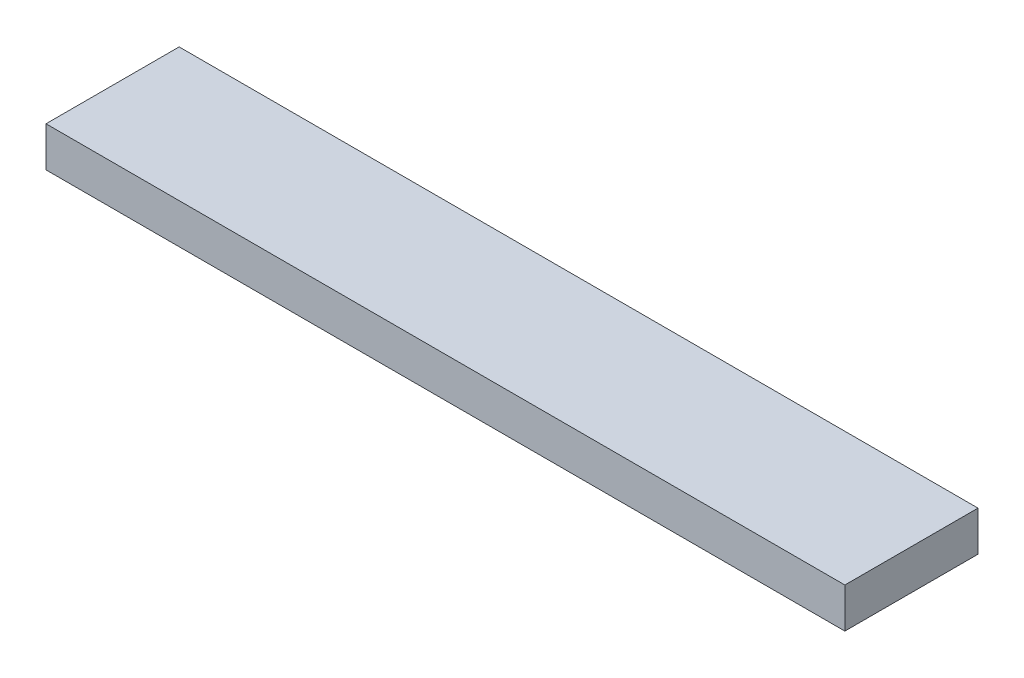
SolidWorks part; units mm, degrees
ref_plane "Front Plane" through (0, 0, 0) normal (0, 0, 1) x (1, 0, 0)
ref_plane "Top Plane" through (0, 0, 0) normal (0, 1, 0) x (1, 0, 0)
ref_plane "Right Plane" through (0, 0, 0) normal (1, 0, 0) x (0, 0, -1)
sketch "Sketch1" plane through (0, 0, 0) normal (0, 1, 0) x (1, 0, 0)
  line L1 (0, 0) -> (-60, 0)
  line L2 (0, 0) -> (0, 10)
  line L3 (0, 10) -> (-60, 10)
  line L4 (-60, 0) -> (-60, 10)
  dimension "D1" = 10
  dimension "D2" = 60
extrude "Boss-Extrude1" add sketch "Sketch1" along normal blind 3
